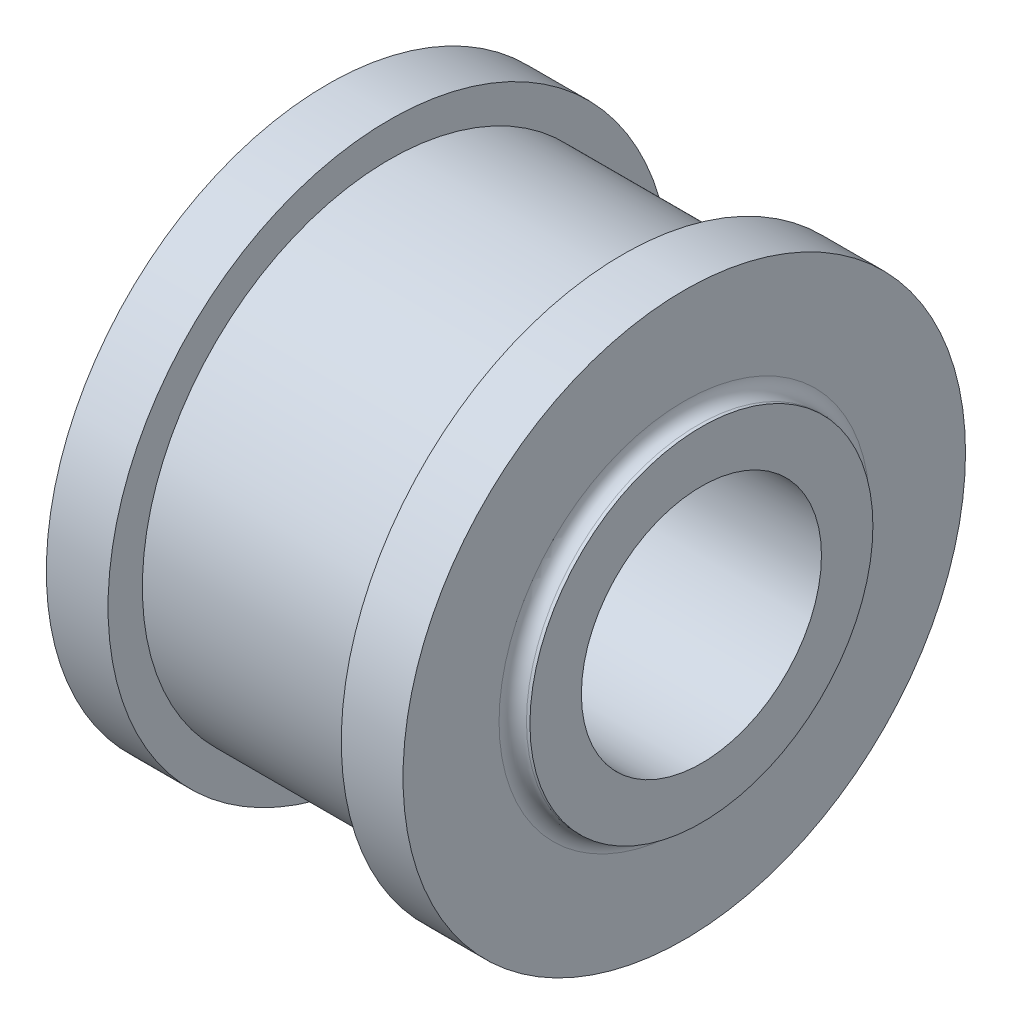
SolidWorks part; units mm, degrees
ref_plane "Front Plane" through (0, 0, 0) normal (0, 0, 1) x (1, 0, 0)
ref_plane "Top Plane" through (0, 0, 0) normal (0, 1, 0) x (1, 0, 0)
ref_plane "Right Plane" through (0, 0, 0) normal (1, 0, 0) x (0, 0, -1)
sketch "Sketch1" plane through (0, 0, 0) normal (0, 0, 1) x (1, 0, 0)
  line L0 (0, 0) -> (-45.0583, 0) construction
  line L1 (-42.7718, 17.5) -> (14.2282, 17.5)
  line L2 (14.2282, 17.5) -> (14.2282, 25)
  line L3 (14.2282, 25) -> (11.7282, 25)
  line L4 (11.7282, 25) -> (11.7282, 41)
  line L5 (11.7282, 41) -> (2.7282, 41)
  line L6 (2.7282, 41) -> (2.7282, 36)
  line L7 (2.7282, 36) -> (-31.2718, 36)
  line L8 (-31.2718, 36) -> (-31.2718, 41)
  line L9 (-31.2718, 41) -> (-40.2718, 41)
  line L10 (-40.2718, 41) -> (-40.2718, 25)
  line L11 (-40.2718, 25) -> (-42.7718, 25)
  line L12 (-42.7718, 25) -> (-42.7718, 17.5)
  line L13 (-14.2718, 17.5) -> (-14.2718, 61.1505) construction
  point P17 (-41.5218, 25)
  point P19 (-27.134, 38.5223)
  point P20 (-25.9456, 35.9476)
  dimension "D1" = 34
  dimension "D2" = 26
  dimension "D3" = 26
  dimension "D4" = 28.5
  dimension "D5" = 17
  dimension "D6" = 17.5
  dimension "D7" = 25
  dimension "D8" = 25
  dimension "D9" = 36
  dimension "D10" = 41
  dimension "D11" = 41
revolve "Revolve1" add sketch "Sketch1" angle 360 about L0
fillet "Fillet1" radius 2 2 edges at (11.7282, 0, -25) (-40.2718, 0, -25)
